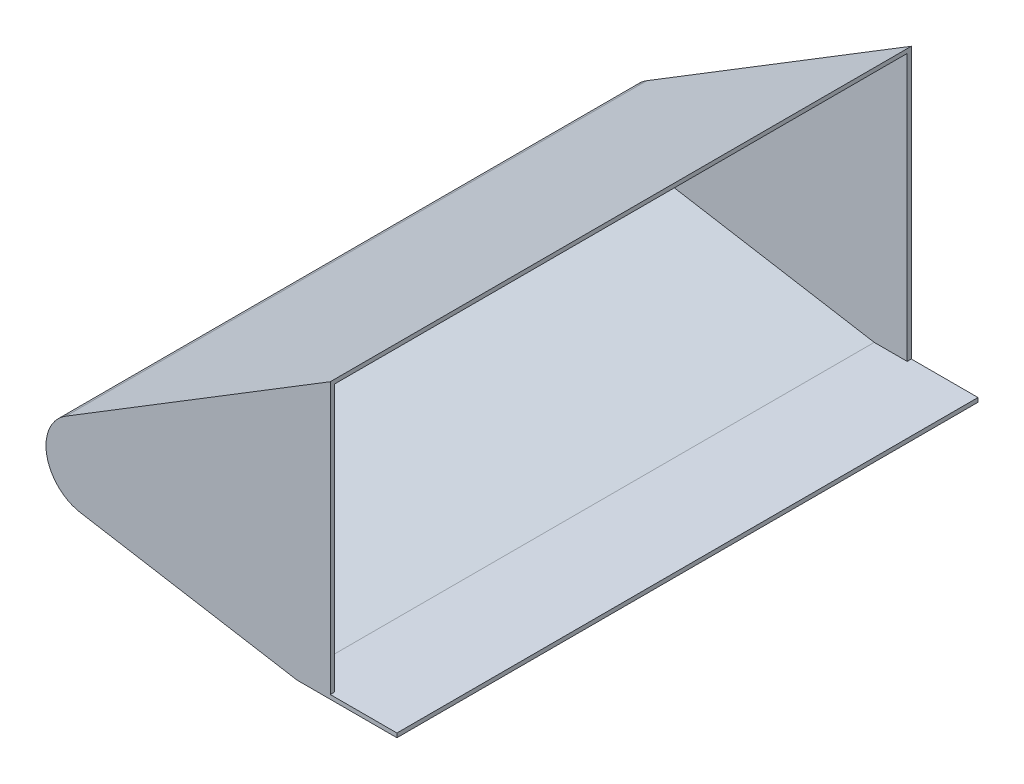
SolidWorks part; units mm, degrees
ref_plane "Front Plane" through (0, 0, 0) normal (0, 0, 1) x (1, 0, 0)
ref_plane "Top Plane" through (0, 0, 0) normal (0, 1, 0) x (1, 0, 0)
ref_plane "Right Plane" through (0, 0, 0) normal (1, 0, 0) x (0, 0, -1)
sketch "Sketch1" plane through (0, 0, 0) normal (0, 0, 1) x (1, 0, 0)
  line L0 (0, 0) -> (-120, 0)
  line L1 (-120, 0) -> (-500.2764, 64.4555)
  line L2 (0, -5) -> (-120.4207, -5)
  line L3 (-120.4207, -5) -> (-505.3513, 60.2443)
  line L4 (0, 0) -> (0, -5)
  line L7 (-506.5931, 65.0877) -> (-80.273, 326.337)
  line L8 (-80.273, 326.337) -> (-80.273, 321.337)
  line L9 (-80.273, 321.337) -> (-500.2764, 64.4555)
  line L10 (-120, 0) -> (-504.5157, 65.174) construction
  line L11 (-506.5931, 65.0877) -> (-434.6902, 65.0877) construction
  line L12 (-506.5931, 65.0877) -> (-512.5152, 61.4586)
  line L13 (-505.3513, 60.2443) -> (-512.5152, 61.4586)
  dimension "D1" = 120
  dimension "D2" = 31.5
  dimension "D3" = 170.38
  dimension "D5" = 5
  dimension "D6" = 500
  dimension "D7" = 5
  dimension "D4" = 5
extrude "Boss-Extrude1" add sketch "Sketch1" along normal blind 700
fillet "Fillet4" radius 50 1 edges at (-500.2764, 64.4555, 350)
fillet "Fillet5" radius 50 1 edges at (-512.5152, 61.4586, 350)
sketch "Sketch2" plane through (0, 0, 700) normal (0, 0, 1) x (1, 0, 0)
  line L4 (-120.4207, -5) -> (-381.0844, 39.1816)
  line L7 (-80.273, 326.337) -> (-398.8537, 131.1105)
  line L11 (-80.273, 326.337) -> (-80.273, 0)
  line L12 (0, 0) -> (-120, 0) construction
  line L13 (-120.4207, -5) -> (-80.273, -5)
  line L14 (-120.4207, -5) -> (0, -5) construction
  line L15 (-80.273, -5) -> (-80.273, 0)
  arc A1 (-398.8537, 131.1105) -> (-381.0844, 39.1816) centre (-372.7288, 88.4784) ccw construction
  spline S1 degree 3 poles (-398.8537, 131.1105) (-406.7061, 126.3374) (-417.397, 114.6682) (-424.2207, 91.7131) (-421.1124, 70.3204) (-406.8826, 49.0488) (-391.3601, 40.8762) (-381.0844, 39.1816) knots 0 0 0 0 0.228119 0.378356 0.583675 0.742973 1 1 1 1
extrude "Boss-Extrude2" add sketch "Sketch2" against normal blind 5
ref_plane "Plane1" through (0, 0, 350) normal (0, 0, 1) x (1, 0, 0)
mirror "Mirror2" about plane through (0, 0, 350) normal (0, 0, 1) of bodies 102
